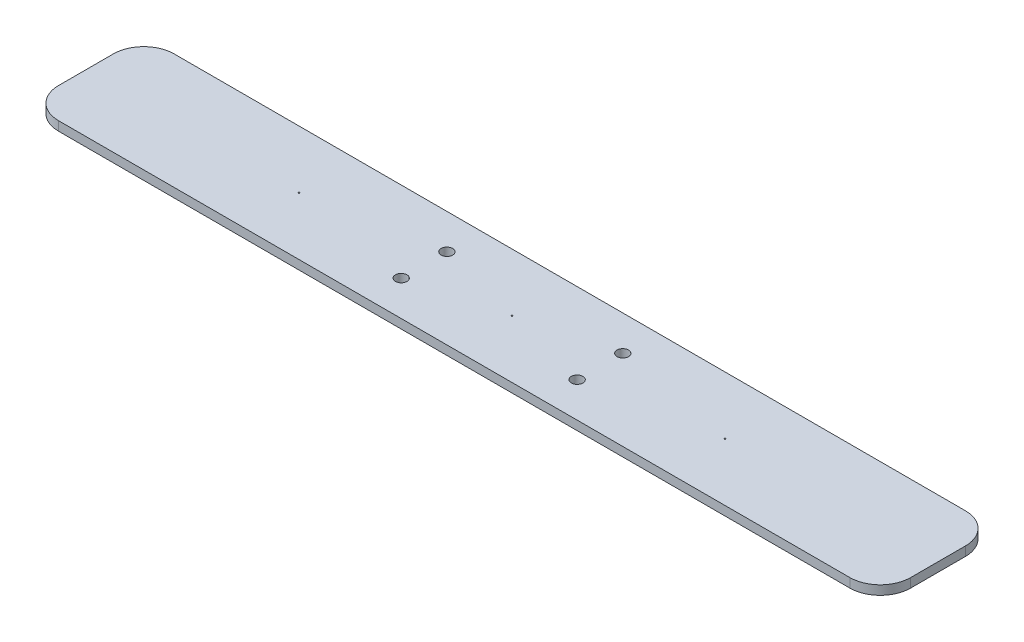
SolidWorks part; units mm, degrees
ref_plane "Front Plane" through (0, 0, 0) normal (0, 0, 1) x (1, 0, 0)
ref_plane "Top Plane" through (0, 0, 0) normal (0, 1, 0) x (1, 0, 0)
ref_plane "Right Plane" through (0, 0, 0) normal (1, 0, 0) x (0, 0, -1)
sketch "Sketch1" plane through (0, 0, 0) normal (0, 1, 0) x (1, 0, 0)
  line L1 (10, 0) -> (270, 0)
  line L2 (0, -10) -> (0, -28)
  line L3 (10, -38) -> (270, -38)
  line L4 (280, -10) -> (280, -28)
  arc A0 (0, -28) -> (10, -38) centre (10, -28) ccw
  arc A1 (270, -38) -> (280, -28) centre (270, -28) ccw
  arc A2 (270, 0) -> (280, -10) centre (270, -10) cw
  arc A3 (10, 0) -> (0, -10) centre (10, -10) ccw
  point P7 (0, -38)
  point P12 (280, 0)
  point P15 (0, 0)
  dimension "D3" = 10
  dimension "D1" = 280
  dimension "D2" = 38
extrude "Boss-Extrude1" add sketch "Sketch1" along normal blind 3
hole_wizard "#6 Clearance Hole1" positions "Sketch2" profile "Sketch3" hole size "#6" standard "ANSI Inch" end condition through all
sketch "Sketch2" plane through (0, 3, 0) normal (0, 1, 0) x (1, 0, 0)
  line L0 (270, 0) -> (10, 0) construction
  line L1 (0, -10) -> (0, -28) construction
  point P0 (111.1, -11.5)
  point P2 (111.1, -26.5)
  point P4 (168.9, -26.5)
  point P6 (168.9, -11.5)
  dimension "D1" = 15
  dimension "D2" = 57.8
  dimension "D3" = 11.5
  dimension "D4" = 111.1
sketch "Sketch3" plane through (111.1, 3, 11.5) normal (1, 0, 0) x (0, 0, 1)
  line L0 (0, 0) -> (0, 3)
  line L1 (0, 3) -> (1.8986, 3)
  line L2 (1.8986, 3) -> (1.8986, 0)
  line L5 (1.8986, 0) -> (0, 0)
  line L11 (0, -6.35) -> (0, 107.95) construction
  dimension "Thru Hole Dia." = 3.7973
  dimension "Thru Hole Depth" = 3
sketch "Sketch4" plane through (0, 3, 0) normal (0, 1, 0) x (1, 0, 0)
  line L0 (280, -28) -> (280, -10) construction
  line L1 (0, -10) -> (0, -28) construction
  circle A0 centre (70, -19) radius 0.25
  circle A1 centre (140, -19) radius 0.25
  circle A2 centre (210, -19) radius 0.25
  point P6 (0, 0)
  point P9 (0, 0)
  point P10 (0, 0)
  point P11 (280, -19)
  point P14 (0, 0)
  point P15 (0, 0)
  point P16 (0, -19)
  point P17 (0, 0)
  point P18 (0, 0)
  dimension "D1" = 0.5
  dimension "D2" = 0.5
  dimension "D3" = 0.5
  dimension "D4" = 70
  dimension "D5" = 70
  dimension "D6" = 70
extrude "Cut-Extrude1" cut sketch "Sketch4" against normal blind 10
equation "\"D3@Sketch2\"=(38-\"D1@Sketch2\")/2"
equation "\"D4@Sketch2\"=(280-\"D2@Sketch2\")/2"
equation "\"D2@Sketch4\"=\"D1@Sketch4\""
equation "\"D3@Sketch4\"=\"D1@Sketch4\""
equation "\"D4@Sketch4\"=280/4"
equation "\"D5@Sketch4\"=\"D4@Sketch4\""
equation "\"D6@Sketch4\"=\"D4@Sketch4\""
